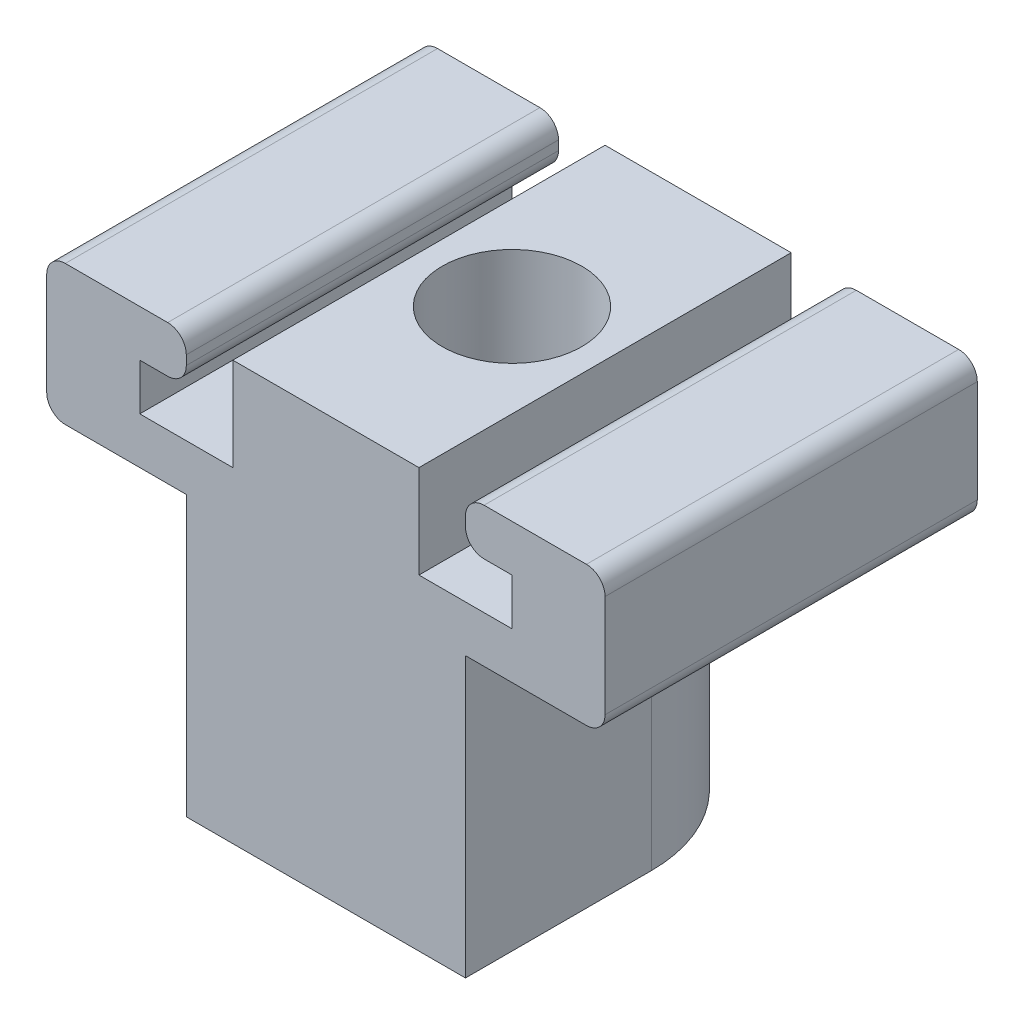
SolidWorks part; units mm, degrees
ref_plane "Front Plane" through (0, 0, 0) normal (0, 0, 1) x (1, 0, 0)
ref_plane "Top Plane" through (0, 0, 0) normal (0, 1, 0) x (1, 0, 0)
ref_plane "Right Plane" through (0, 0, 0) normal (1, 0, 0) x (0, 0, -1)
sketch "Sketch1" plane through (0, 0, 0) normal (0, 1, 0) x (1, 0, 0)
  line L1 (-19.05, -12.7) -> (19.05, -12.7)
  line L2 (-19.05, -12.7) -> (-19.05, 12.7)
  line L3 (-19.05, 12.7) -> (19.05, 12.7)
  line L4 (19.05, -12.7) -> (19.05, 12.7)
  line L5 (-19.05, -12.7) -> (19.05, 12.7) construction
  line L6 (-19.05, 12.7) -> (19.05, -12.7) construction
  point P0 (0, 0)
  dimension "D1" = 25.4
  dimension "D2" = 38.1
extrude "Boss-Extrude1" add sketch "Sketch1" along normal blind 9.525
ref_plane "Plane1" through (0, 0, 0) normal (1, 0, 0) x (0, 0, -1)
sketch "Sketch2" plane through (0, 0, -12.7) normal (0, 0, -1) x (-1, 0, 0)
  line L0 (-9.525, 9.525) -> (-9.525, 6.35)
  line L1 (-19.05, 9.525) -> (19.05, 9.525) construction
  line L2 (-6.35, 9.525) -> (-6.35, 3.175)
  line L3 (-9.525, 6.35) -> (-12.7, 6.35)
  line L4 (-12.7, 6.35) -> (-12.7, 3.175)
  line L5 (-12.7, 3.175) -> (-6.35, 3.175)
  line L6 (-19.05, 9.525) -> (-19.05, 0) construction
  line L7 (-6.35, 9.525) -> (-9.525, 9.525)
  dimension "D1" = 9.525
  dimension "D2" = 3.175
  dimension "D3" = 3.175
  dimension "D4" = 6.35
  dimension "D5" = 3.175
extrude "Cut-Extrude1" cut sketch "Sketch2" against normal up to next
mirror "Mirror1" about plane through (0, 0, 0) normal (1, 0, 0) of "Cut-Extrude1"
sketch "Sketch3" plane through (0, 0, 0) normal (0, -1, 0) x (1, 0, 0)
  line L1 (9.525, 0) -> (9.525, 12.7)
  line L2 (-19.05, 12.7) -> (19.05, 12.7) construction
  line L4 (-9.525, 0) -> (-9.525, 12.7)
  line L5 (-9.525, 12.7) -> (9.525, 12.7)
  arc A0 (9.525, 0) -> (-9.525, 0) centre (0, 0) cw
  dimension "D1" = 19.05
extrude "Boss-Extrude2" add sketch "Sketch3" along normal blind 19.05
sketch "Sketch5" plane through (0, -19.05, 0) normal (0, -1, 0) x (-1, 0, 0)
  circle A0 centre (0, 0) radius 4.7625
  dimension "D1" = 9.525
extrude "Cut-Extrude3" cut sketch "Sketch5" against normal up to next
sketch "Sketch4" plane through (0, -19.05, 0) normal (0, -1, 0) x (1, 0, 0)
  circle A0 centre (0, 0) radius 7.1438
  dimension "D1" = 14.2875
extrude "Cut-Extrude2" cut sketch "Sketch4" against normal blind 19.05
fillet "Fillet2" radius 1.27 8 edges at (19.05, 0, 0) (-19.05, 0, 0) (-19.05, 9.525, 0) (19.05, 9.525, 0) (9.525, 6.35, 0) (9.525, 9.525, 0) (-9.525, 6.35, 0) (-9.525, 9.525, 0)
